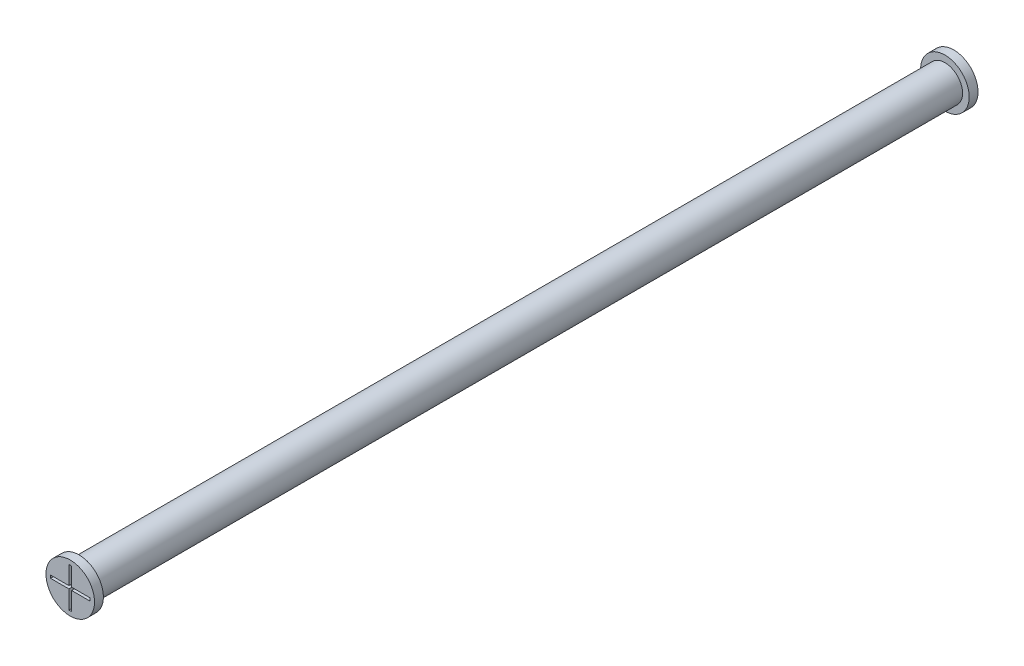
SolidWorks part; units mm, degrees
material "Cast Alloy Steel"
ref_plane "Front Plane" through (0, 0, 0) normal (0, 0, 1) x (1, 0, 0)
ref_plane "Top Plane" through (0, 0, 0) normal (0, 1, 0) x (1, 0, 0)
ref_plane "Right Plane" through (0, 0, 0) normal (1, 0, 0) x (0, 0, -1)
sketch "Sketch1" plane through (0, 0, 0) normal (0, 0, 1) x (1, 0, 0)
  circle A0 centre (0, 0) radius 2
extrude "Boss-Extrude1" add sketch "Sketch1" along normal blind 98
sketch "Sketch2" plane through (0, 0, 98) normal (0, 0, 1) x (1, 0, 0)
  circle A0 centre (0, 0) radius 2.75
extrude "Boss-Extrude2" add sketch "Sketch2" along normal blind 1
sketch "Sketch3" plane through (0, 0, 0) normal (0, 0, -1) x (-1, 0, 0)
  circle A0 centre (0, 0) radius 2.75
extrude "Boss-Extrude3" add sketch "Sketch3" along normal blind 1
sketch "Sketch4" plane through (0, 0, -1) normal (0, 0, -1) x (-1, 0, 0)
  line L0 (-0.1549, -0.1609) -> (-0.1549, -2.2347)
  line L1 (-2.2347, 0.1609) -> (-0.1549, 0.1609)
  line L2 (-2.2347, 0.1609) -> (-2.2347, -0.1609)
  line L3 (-2.2347, -0.1609) -> (-0.1549, -0.1609)
  line L4 (2.2347, 0.1609) -> (2.2347, -0.1609)
  line L7 (-0.1549, 2.2347) -> (0.1549, 2.2347)
  line L8 (-0.1549, 2.2347) -> (-0.1549, 0.1609)
  line L9 (-0.1549, -2.2347) -> (0.1549, -2.2347)
  line L10 (0.1549, 2.2347) -> (0.1549, 0.1609)
  line L13 (0.1549, 0.1609) -> (2.2347, 0.1609)
  line L15 (0.1549, -0.1609) -> (0.1549, -2.2347)
  line L16 (0.1549, -0.1609) -> (2.2347, -0.1609)
  point P0 (0, 0)
  point P6 (0, 0)
extrude "Cut-Extrude1" cut sketch "Sketch4" against normal blind 0.5
sketch "Sketch5" plane through (0, 0, 99) normal (0, 0, 1) x (1, 0, 0)
  line L12 (-2.2347, -0.1609) -> (-0.1549, -0.1609)
  line L13 (-2.2347, 0.1609) -> (-2.2347, -0.1609)
  line L14 (-0.1549, 0.1609) -> (-2.2347, 0.1609)
  line L15 (-0.1549, 2.2347) -> (-0.1549, 0.1609)
  line L16 (0.1549, 2.2347) -> (-0.1549, 2.2347)
  line L17 (0.1549, 0.1609) -> (0.1549, 2.2347)
  line L18 (2.2347, 0.1609) -> (0.1549, 0.1609)
  line L19 (2.2347, -0.1609) -> (2.2347, 0.1609)
  line L20 (0.1549, -0.1609) -> (2.2347, -0.1609)
  line L21 (0.1549, -2.2347) -> (0.1549, -0.1609)
  line L22 (-0.1549, -2.2347) -> (0.1549, -2.2347)
  line L23 (-0.1549, -0.1609) -> (-0.1549, -2.2347)
  line L24 (-2.2347, -0.1609) -> (-0.1549, -0.1609)
  line L25 (-2.2347, 0.1609) -> (-2.2347, -0.1609)
  line L26 (-0.1549, 0.1609) -> (-2.2347, 0.1609)
  line L27 (-0.1549, 2.2347) -> (-0.1549, 0.1609)
  line L28 (0.1549, 2.2347) -> (-0.1549, 2.2347)
  line L29 (0.1549, 0.1609) -> (0.1549, 2.2347)
  line L30 (2.2347, 0.1609) -> (0.1549, 0.1609)
  line L31 (2.2347, -0.1609) -> (2.2347, 0.1609)
  line L32 (0.1549, -0.1609) -> (2.2347, -0.1609)
  line L33 (0.1549, -2.2347) -> (0.1549, -0.1609)
  line L34 (-0.1549, -2.2347) -> (0.1549, -2.2347)
  line L35 (-0.1549, -0.1609) -> (-0.1549, -2.2347)
  dimension "D1" = 0
extrude "Cut-Extrude2" cut sketch "Sketch5" against normal blind 0.5
